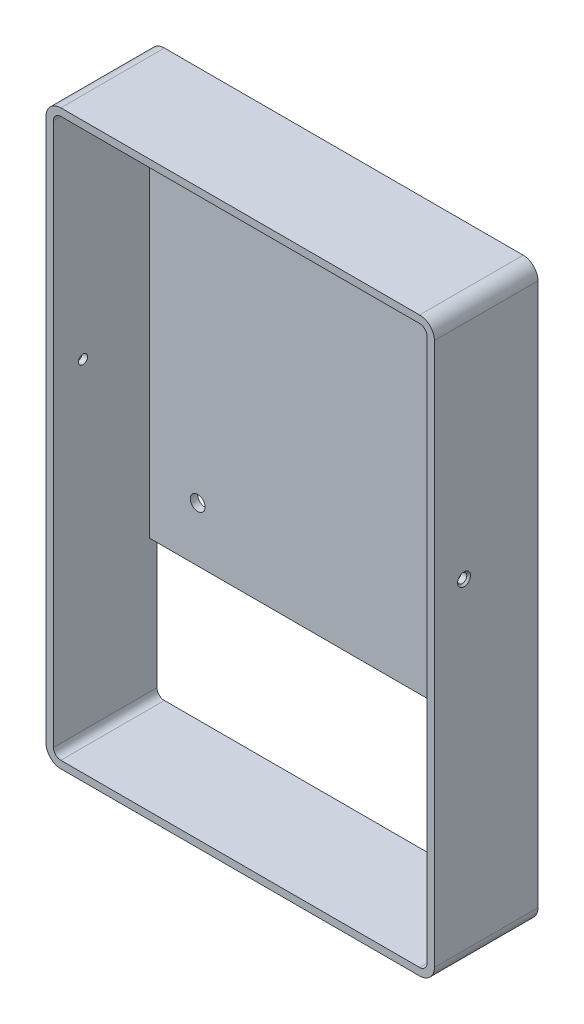
SolidWorks part; units mm, degrees
ref_plane "Front Plane" through (0, 0, 0) normal (0, 0, 1) x (1, 0, 0)
ref_plane "Top Plane" through (0, 0, 0) normal (0, 1, 0) x (1, 0, 0)
ref_plane "Right Plane" through (0, 0, 0) normal (1, 0, 0) x (0, 0, -1)
sketch "Sketch1" plane through (0, 0, 0) normal (0, 0, 1) x (1, 0, 0)
  line L0 (-50.5, 59.875) -> (-50.5, -86.875) construction
  line L1 (-50, 61.375) -> (50, 61.375) construction
  line L2 (-50, 61.375) -> (-50, -61.375) construction
  line L3 (-50, -61.375) -> (50, -61.375) construction
  line L4 (50, 61.375) -> (50, -61.375) construction
  line L5 (-50, 61.375) -> (50, -61.375) construction
  line L6 (-50, -61.375) -> (50, 61.375) construction
  line L7 (-48.5, -88.875) -> (48.5, -88.875) construction
  line L8 (50.5, 59.875) -> (50.5, -86.875) construction
  line L9 (-48.5, 61.875) -> (48.5, 61.875) construction
  line L14 (-48.5, 63.875) -> (48.5, 63.875)
  line L15 (52.5, 59.875) -> (52.5, -86.875)
  line L16 (-48.5, -90.875) -> (48.5, -90.875)
  line L17 (-52.5, 59.875) -> (-52.5, -86.875)
  arc A1 (48.5, -88.875) -> (50.5, -86.875) centre (48.5, -86.875) ccw construction
  arc A2 (50.5, 59.875) -> (48.5, 61.875) centre (48.5, 59.875) ccw construction
  arc A4 (-48.5, -88.875) -> (-50.5, -86.875) centre (-48.5, -86.875) cw construction
  arc A5 (-48.5, 61.875) -> (-50.5, 59.875) centre (-48.5, 59.875) ccw construction
  arc A6 (52.5, 59.875) -> (48.5, 63.875) centre (48.5, 59.875) ccw
  arc A7 (48.5, -90.875) -> (52.5, -86.875) centre (48.5, -86.875) ccw
  arc A8 (-48.5, -90.875) -> (-52.5, -86.875) centre (-48.5, -86.875) cw
  arc A9 (-52.5, 59.875) -> (-48.5, 63.875) centre (-48.5, 59.875) cw
  point P0 (0, 0)
  dimension "D4" = 2
  dimension "D12" = 2
  dimension "D13" = 2
  dimension "D14" = 4
  dimension "D15" = 4
  dimension "D1" = 100
  dimension "D2" = 122.75
  dimension "D3" = 0.5
  dimension "D5" = 0.5
  dimension "D6" = 0.5
  dimension "D7" = 27.5
  dimension "D8" = 2
  dimension "D9" = 2
  dimension "D10" = 2
  dimension "D11" = 2
extrude "Boss-Extrude1" add sketch "Sketch1" against normal blind 28
shell "Shell1" thickness 2
ref_plane "Plane1" through (0, 0, -6) normal (0, 0, 1) x (1, 0, 0)
sketch "Sketch2" plane through (0, 0, -28) normal (0, 0, -1) x (-1, 0, 0)
  line L4 (48.5, 63.875) -> (-48.5, 63.875) construction
  line L5 (-52.5, 59.875) -> (-52.5, -86.875) construction
  line L6 (52.5, 59.875) -> (52.5, -86.875) construction
  line L7 (-50.5, -50.875) -> (50.5, -50.875)
  line L8 (-50.5, 59.875) -> (-50.5, -86.875) construction
  line L9 (50.5, 59.875) -> (50.5, -86.875) construction
  line L10 (-50.5, -50.875) -> (-50.5, -86.875)
  line L11 (48.5, -88.875) -> (-48.5, -88.875) construction
  line L12 (50.5, -50.875) -> (50.5, -86.875)
  line L13 (48.5, -88.875) -> (-48.5, -88.875)
  line L14 (48.5, -90.875) -> (-48.5, -90.875) construction
  circle A0 centre (-37.5, 48.875) radius 2
  circle A1 centre (37.5, 48.875) radius 2
  circle A2 centre (37.5, -36.125) radius 2
  circle A3 centre (-37.5, -36.125) radius 2
  arc A5 (-50.5, -86.875) -> (-48.5, -88.875) centre (-48.5, -86.875) ccw construction
  arc A6 (48.5, -88.875) -> (50.5, -86.875) centre (48.5, -86.875) ccw
  arc A7 (-50.5, -86.875) -> (-48.5, -88.875) centre (-48.5, -86.875) ccw
  arc A8 (48.5, -88.875) -> (50.5, -86.875) centre (48.5, -86.875) ccw construction
  dimension "D2" = 15
  dimension "D3" = 15
  dimension "D4" = 85
  dimension "D5" = 4
  dimension "D6" = 40
  dimension "D1" = 15
extrude "Cut-Extrude1" cut sketch "Sketch2" against normal blind 10
hole_wizard "M3 Tapped Hole1" positions "Sketch3" profile "Sketch4" tap size "M3" standard "ISO"
sketch "Sketch3" plane through (52.5, 0, 0) normal (1, 0, 0) x (0, 0, -1)
  line L0 (0, 59.875) -> (0, -86.875) construction
  point P0 (8, 0)
  dimension "D1" = 8
sketch "Sketch4" plane through (52.5, 0, -8) normal (0, 1, 0) x (0, 0, -1)
  line L0 (0, 0) -> (0, 2)
  line L1 (0, 2) -> (1.25, 2)
  line L2 (1.25, 2) -> (1.25, 0.5)
  line L3 (1.25, 0.5) -> (1.75, 0)
  line L5 (1.75, 0) -> (0, 0)
  line L6 (-1.25, 0.5) -> (-1.75, 0) construction
  line L11 (0, -6.35) -> (0, 107.95) construction
  dimension "Thru Tap Drill Dia." = 2.5
  dimension "Thru Tap Drill Depth" = 2
  dimension "Near C'Sink Dia." = 3.5
  dimension "Near C'Sink Angle" = 90
cosmetic thread "Hole Thread2" parameters "D2"=3
hole_wizard "M3 Tapped Hole2" positions "Sketch5" profile "Sketch6" tap size "M3" standard "ISO" end condition up to next
sketch "Sketch5" plane through (-52.5, 0, 0) normal (-1, 0, 0) x (0, 0, 1)
  line L0 (0, 59.875) -> (0, -86.875) construction
  point P0 (-8, 0)
  dimension "D1" = 8
sketch "Sketch6" plane through (-52.5, 0, -8) normal (0, 1, 0) x (0, 0, 1)
  line L0 (0, 0) -> (0, 2)
  line L1 (0, 2) -> (1.25, 2)
  line L2 (1.25, 2) -> (1.25, 0.5)
  line L3 (1.25, 0.5) -> (1.75, 0)
  line L5 (1.75, 0) -> (0, 0)
  line L6 (-1.25, 0.5) -> (-1.75, 0) construction
  line L11 (0, -6.35) -> (0, 107.95) construction
  dimension "Thru Tap Drill Dia." = 2.5
  dimension "Thru Tap Drill Depth" = 2
  dimension "Near C'Sink Dia." = 3.5
  dimension "Near C'Sink Angle" = 90
cosmetic thread "Hole Thread3" parameters "D2"=3
